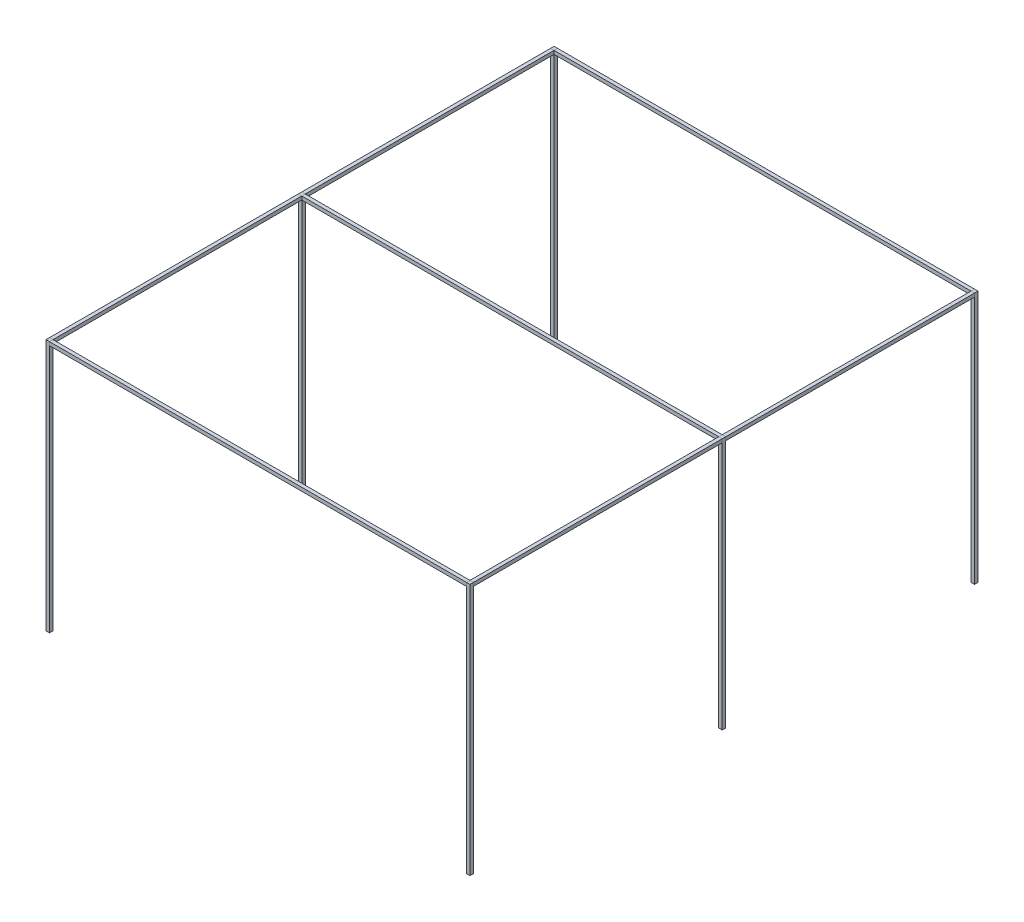
SolidWorks part; units mm, degrees
ref_plane "Front Plane" through (0, 0, 0) normal (0, 0, 1) x (1, 0, 0)
ref_plane "Top Plane" through (0, 0, 0) normal (0, 1, 0) x (1, 0, 0)
ref_plane "Right Plane" through (0, 0, 0) normal (1, 0, 0) x (0, 0, -1)
sketch3d "3DSketch1"
  line L0 (0, 0, 0) -> (0, 1828.8, 0)
  line L1 (0, 1828.8, 0) -> (3048, 1828.8, 0)
  line L2 (3048, 1828.8, 0) -> (3048, 0, 0)
  line L3 (0, 1828.8, 0) -> (0, 1828.8, 1828.8)
  line L4 (0, 1828.8, 1828.8) -> (3048, 1828.8, 1828.8)
  line L5 (3048, 1828.8, 1828.8) -> (3048, 1828.8, 0)
  line L6 (0, 1828.8, 1828.8) -> (0, 0, 1828.8)
  line L7 (3048, 1828.8, 1828.8) -> (3048, 0, 1828.8)
  line L8 (0, 1828.8, 1828.8) -> (0, 1828.8, 3657.6)
  line L9 (0, 1828.8, 3657.6) -> (3048, 1828.8, 3657.6)
  line L10 (3048, 1828.8, 3657.6) -> (3048, 1828.8, 1828.8)
  line L11 (3048, 1828.8, 3657.6) -> (3048, 0, 3657.6)
  line L12 (0, 1828.8, 3657.6) -> (0, 0, 3657.6)
  dimension "D1" = 3048
  dimension "D2" = 1828.8
  dimension "D3" = 1828.8
  dimension "D4" = 1828.8
sketch "Sketch1" plane through (0, 0, 0) normal (0, 1, 0) x (1, 0, 0)
  line L0 (1524, 0) -> (1524, -3657.6) construction
  line L1 (-12.7, -3644.9) -> (12.7, -3644.9)
  line L2 (-12.7, -3644.9) -> (-12.7, -3670.3)
  line L3 (-12.7, -3670.3) -> (12.7, -3670.3)
  line L4 (12.7, -3644.9) -> (12.7, -3670.3)
  line L5 (-12.7, -3644.9) -> (12.7, -3670.3) construction
  line L6 (-12.7, -3670.3) -> (12.7, -3644.9) construction
  line L7 (-12.7, -1816.1) -> (12.7, -1816.1)
  line L8 (-12.7, -1816.1) -> (-12.7, -1841.5)
  line L9 (-12.7, -1841.5) -> (12.7, -1841.5)
  line L10 (12.7, -1816.1) -> (12.7, -1841.5)
  line L11 (-12.7, -1816.1) -> (12.7, -1841.5) construction
  line L12 (-12.7, -1841.5) -> (12.7, -1816.1) construction
  line L13 (-12.7, 12.7) -> (12.7, 12.7)
  line L14 (-12.7, 12.7) -> (-12.7, -12.7)
  line L15 (-12.7, -12.7) -> (12.7, -12.7)
  line L16 (12.7, 12.7) -> (12.7, -12.7)
  line L17 (-12.7, 12.7) -> (12.7, -12.7) construction
  line L18 (-12.7, -12.7) -> (12.7, 12.7) construction
  line L19 (0, 0) -> (3048, 0) construction
  line L20 (0, -3657.6) -> (3048, -3657.6) construction
  line L21 (3060.7, -3644.9) -> (3035.3, -3644.9)
  line L22 (3035.3, -3644.9) -> (3035.3, -3670.3)
  line L23 (3060.7, -3644.9) -> (3060.7, -3670.3)
  line L24 (3060.7, -3670.3) -> (3035.3, -3670.3)
  line L25 (3060.7, -1816.1) -> (3035.3, -1816.1)
  line L26 (3035.3, -1816.1) -> (3035.3, -1841.5)
  line L27 (3060.7, -1816.1) -> (3060.7, -1841.5)
  line L28 (3060.7, -1841.5) -> (3035.3, -1841.5)
  line L29 (3035.3, 12.7) -> (3035.3, -12.7)
  line L30 (3060.7, 12.7) -> (3035.3, 12.7)
  line L31 (3060.7, 12.7) -> (3060.7, -12.7)
  line L32 (3060.7, -12.7) -> (3035.3, -12.7)
  point P0 (0, -3657.6)
  point P6 (0, -1828.8)
  point P12 (0, 0)
  dimension "D1" = 25.4
  dimension "D2" = 25.4
  dimension "D3" = 25.4
  dimension "D4" = 25.4
  dimension "D5" = 25.4
  dimension "D6" = 25.4
extrude "Boss-Extrude1" add sketch "Sketch1" along normal blind 1828.8 contours L16 L13 L14 L15 | L28 L27 L25 L26 | L10 L7 L8 L9 | L4 L1 L2 L3 | L24 L23 L21 L22 | L32 L29 L30 L31
sketch "Sketch2" plane through (0, 0, 12.7) normal (0, 0, 1) x (1, 0, 0)
  line L0 (12.7, 1828.8) -> (12.7, 0) construction
  line L1 (-12.7, 1828.8) -> (12.7, 1828.8)
  line L2 (-12.7, 1828.8) -> (-12.7, 1803.4)
  line L3 (-12.7, 1803.4) -> (12.7, 1803.4)
  line L4 (12.7, 1828.8) -> (12.7, 1803.4)
  line L5 (1524, 1828.8) -> (1524, 0) construction
  line L6 (0, 1828.8) -> (3048, 1828.8) construction
  line L7 (3035.3, 1828.8) -> (3035.3, 1803.4)
  line L8 (3060.7, 1828.8) -> (3035.3, 1828.8)
  line L9 (3060.7, 1828.8) -> (3060.7, 1803.4)
  line L10 (3060.7, 1803.4) -> (3035.3, 1803.4)
  dimension "D1" = 25.4
extrude "Boss-Extrude2" add sketch "Sketch2" along normal up to surface (1803.4 mm away) separate body up to face at (0, 914.4, 1816.1)
sketch "Sketch3" plane through (0, 0, 1841.5) normal (0, 0, 1) x (1, 0, 0)
  line L0 (12.7, 1828.8) -> (12.7, 0) construction
  line L1 (-12.7, 1828.8) -> (12.7, 1828.8)
  line L2 (-12.7, 1828.8) -> (-12.7, 1803.4)
  line L3 (-12.7, 1803.4) -> (12.7, 1803.4)
  line L4 (12.7, 1828.8) -> (12.7, 1803.4)
  line L5 (1524, 1828.8) -> (1524, 0) construction
  line L6 (0, 1828.8) -> (3048, 1828.8) construction
  line L7 (3060.7, 1828.8) -> (3060.7, 1803.4)
  line L8 (3060.7, 1828.8) -> (3035.3, 1828.8)
  line L9 (3035.3, 1828.8) -> (3035.3, 1803.4)
  line L10 (3060.7, 1803.4) -> (3035.3, 1803.4)
  dimension "D1" = 25.4
extrude "Boss-Extrude3" add sketch "Sketch3" along normal up to surface (1803.4 mm away) separate body up to face at (3048, 914.4, 3644.9)
sketch "Sketch4" plane through (3035.3, 0, 0) normal (-1, 0, 0) x (0, 0, 1)
  line L0 (1841.5, 1828.8) -> (1841.5, 0) construction
  line L1 (-12.7, 1828.8) -> (12.7, 1828.8)
  line L2 (-12.7, 1828.8) -> (-12.7, 1803.4)
  line L3 (-12.7, 1803.4) -> (12.7, 1803.4)
  line L4 (12.7, 1828.8) -> (12.7, 1803.4)
  line L5 (1816.1, 1828.8) -> (1841.5, 1828.8)
  line L6 (1816.1, 1828.8) -> (1816.1, 1803.4)
  line L7 (1816.1, 1803.4) -> (1841.5, 1803.4)
  line L8 (1841.5, 1828.8) -> (1841.5, 1803.4)
  line L9 (1841.5, 1828.8) -> (1841.5, 1803.4) construction
  line L10 (3670.3, 1828.8) -> (3670.3, 0) construction
  line L11 (3644.9, 1828.8) -> (3670.3, 1828.8)
  line L12 (3644.9, 1828.8) -> (3644.9, 1803.4)
  line L13 (3644.9, 1803.4) -> (3670.3, 1803.4)
  line L14 (3670.3, 1828.8) -> (3670.3, 1803.4)
extrude "Boss-Extrude4" add sketch "Sketch4" along normal up to surface (3022.6 mm away) separate body up to face at (12.7, 1816.1, 914.4)
